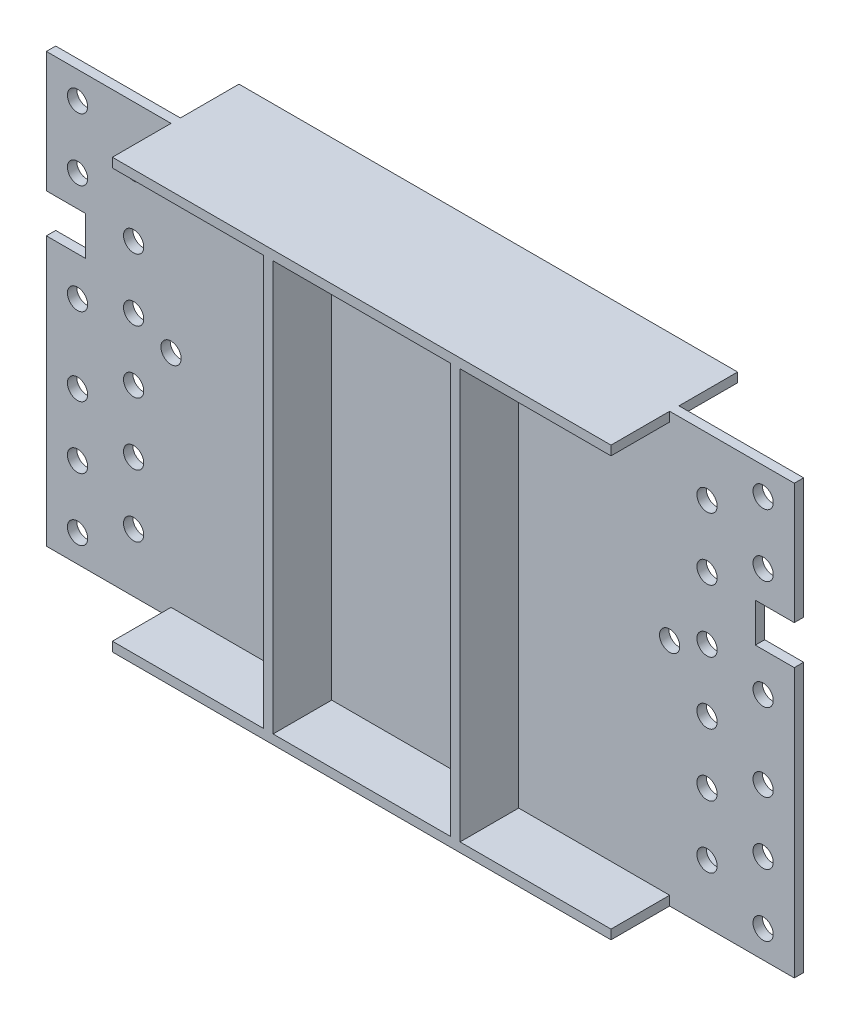
SolidWorks part; units mm, degrees
ref_plane "前视基准面" through (0, 0, 0) normal (0, 0, 1) x (1, 0, 0)
ref_plane "上视基准面" through (0, 0, 0) normal (0, 1, 0) x (1, 0, 0)
ref_plane "右视基准面" through (0, 0, 0) normal (1, 0, 0) x (0, 0, -1)
sketch "草图1" plane through (0, 0, 0) normal (0, 0, 1) x (1, 0, 0)
  line L1 (0, 0) -> (960, 0)
  line L2 (0, 0) -> (0, 550)
  line L3 (0, 550) -> (960, 550)
  line L4 (960, 0) -> (960, 550)
  dimension "D1" = 960
  dimension "D2" = 550
extrude "凸台-拉伸1" add sketch "草图1" along normal blind 12
sketch "草图2" plane through (0, 550, 0) normal (0, 1, 0) x (1, 0, 0)
  line L0 (480, -1012) -> (480, 48988) construction
  line L1 (960, -12) -> (0, -12) construction
  line L2 (-1000, -6) -> (49000, -6) construction
  line L3 (0, -12) -> (0, 0) construction
  line L5 (160, 75.25) -> (800, 75.25)
  line L6 (160, 75.25) -> (160, -87.25)
  line L7 (160, -87.25) -> (800, -87.25)
  line L8 (800, 75.25) -> (800, -87.25)
  point P5 (480, -12)
  point P10 (0, -6)
  dimension "D1" = 640
  dimension "D2" = 162.5
extrude "凸台-拉伸2" add sketch "草图2" against normal blind 12
sketch "草图3" plane through (0, 0, 0) normal (0, -1, 0) x (1, 0, 0)
  line L1 (160, 87.25) -> (800, 87.25)
  line L2 (160, 87.25) -> (160, -75.25)
  line L3 (160, -75.25) -> (800, -75.25)
  line L4 (800, 87.25) -> (800, -75.25)
extrude "凸台-拉伸3" add sketch "草图3" against normal blind 12
sketch "草图4" plane through (0, 0, -75.25) normal (0, 0, -1) x (-1, 0, 0)
  line L0 (-160, 538) -> (-800, 538) construction
  line L1 (-606.25, 538) -> (-593.75, 538)
  line L2 (-606.25, 538) -> (-606.25, 12)
  line L3 (-606.25, 12) -> (-593.75, 12)
  line L4 (-593.75, 538) -> (-593.75, 12)
  line L5 (-160, 12) -> (-800, 12) construction
  line L6 (-366.25, 538) -> (-353.75, 538)
  line L7 (-366.25, 538) -> (-366.25, 12)
  line L8 (-366.25, 12) -> (-353.75, 12)
  line L9 (-353.75, 538) -> (-353.75, 12)
  line L10 (-480, -450) -> (-480, 49550) construction
  line L11 (-800, 550) -> (-160, 550) construction
  line L12 (-600, -450) -> (-600, 49550) construction
  line L13 (-360, -450) -> (-360, 49550) construction
  point P17 (-480, 550)
  dimension "D1" = 12.5
  dimension "D2" = 12.5
  dimension "D3" = 120
  dimension "D4" = 120
extrude "凸台-拉伸4" add sketch "草图4" against normal blind 162.5
ref_plane "基准面1" through (480, 0, 0) normal (-1, 0, 0) x (0, 0, 1)
sketch "草图5" plane through (0, 0, 12) normal (0, 0, 1) x (1, 0, 0)
  line L0 (40, -655.2641) -> (40, 49344.7359) construction
  line L1 (112, -678.3072) -> (112, 49321.6928) construction
  line L2 (0, 550) -> (0, 0) construction
  line L3 (160, 550) -> (0, 550) construction
  line L5 (0, 0) -> (160, 0) construction
  circle A0 centre (40, 515) radius 13
  circle A1 centre (40, 435) radius 13
  circle A2 centre (40, 295) radius 13
  circle A3 centre (40, 35) radius 13
  circle A4 centre (112, 235) radius 13
  circle A5 centre (112, 155) radius 13
  circle A6 centre (112, 475) radius 13
  circle A7 centre (112, 395) radius 13
  circle A8 centre (112, 315) radius 13
  circle A9 centre (112, 75) radius 13
  circle A10 centre (40, 195) radius 13
  circle A11 centre (40, 115) radius 13
  circle A12 centre (160, 295) radius 13
  dimension "D3" = 26
  dimension "D1" = 40
  dimension "D2" = 72
  dimension "D4" = 35
  dimension "D5" = 40
  dimension "D6" = 40
  dimension "D7" = 40
  dimension "D8" = 80
  dimension "D9" = 20
  dimension "D10" = 35
  dimension "D11" = 60
  dimension "D12" = 80
  dimension "D13" = 80
  dimension "D14" = 80
  dimension "D15" = 80
  dimension "D16" = 120
extrude "切除-拉伸1" cut sketch "草图5" against normal through all
mirror "镜向1" about plane through (480, 0, 0) normal (-1, 0, 0) of "切除-拉伸1"
sketch "草图6" plane through (0, 0, 0) normal (0, 0, -1) x (-1, 0, 0)
  line L0 (0, 550) -> (0, 0) construction
  line L1 (-50, 395) -> (0, 395)
  line L2 (-50, 395) -> (-50, 345)
  line L3 (-50, 345) -> (0, 345)
  line L4 (0, 395) -> (0, 345)
  line L5 (-1112, 395) -> (48888, 395) construction
  line L6 (-960, 0) -> (-960, 550) construction
  line L7 (-960, 395) -> (-910, 395)
  line L8 (-960, 395) -> (-960, 345)
  line L9 (-960, 345) -> (-910, 345)
  line L10 (-910, 395) -> (-910, 345)
  dimension "D1" = 50
  dimension "D2" = 50
  dimension "D3" = 50
  dimension "D4" = 50
extrude "切除-拉伸2" cut sketch "草图6" against normal through all
